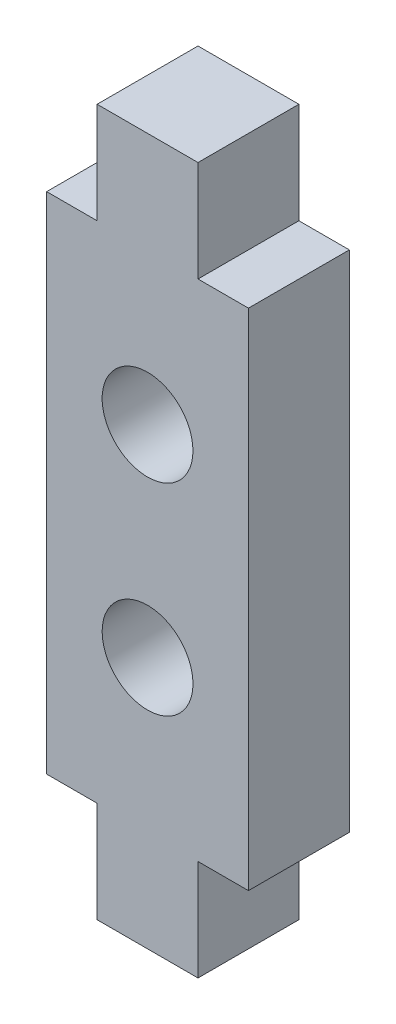
SolidWorks part; units mm, degrees
ref_plane "Front Plane" through (0, 0, 0) normal (0, 0, 1) x (1, 0, 0)
ref_plane "Top Plane" through (0, 0, 0) normal (0, 1, 0) x (1, 0, 0)
ref_plane "Right Plane" through (0, 0, 0) normal (1, 0, 0) x (0, 0, -1)
sketch "Sketch1" plane through (0, 0, 0) normal (0, 0, 1) x (1, 0, 0)
  line L0 (2.5, -7.5) -> (5, -7.5)
  line L1 (-5, 17.5) -> (-2.5, 17.5)
  line L2 (-5, 17.5) -> (-5, -7.5)
  line L3 (-5, -7.5) -> (-2.5, -7.5)
  line L4 (5, 17.5) -> (5, -7.5)
  line L5 (5, 5) -> (-5, 5) construction
  line L6 (2.5, 22.5) -> (2.5, 17.5)
  line L7 (-2.5, -12.5) -> (2.5, -12.5)
  line L8 (-2.5, -12.5) -> (-2.5, -7.5)
  line L9 (-2.5, 22.5) -> (2.5, 22.5)
  line L10 (2.5, -12.5) -> (2.5, -7.5)
  line L11 (-2.5, 22.5) -> (-2.5, 17.5)
  line L12 (2.5, 17.5) -> (5, 17.5)
  circle A0 centre (0, 10) radius 2.25
  circle A1 centre (0, 0) radius 2.25
  point P0 (0, 0)
  point P5 (0, -7.5)
  point P19 (0, 0)
  dimension "D3" = 5
  dimension "D4" = 4.5
  dimension "D1" = 25
  dimension "D2" = 10
  dimension "D5" = 10
extrude "Boss-Extrude1" add sketch "Sketch1" along normal blind 5
